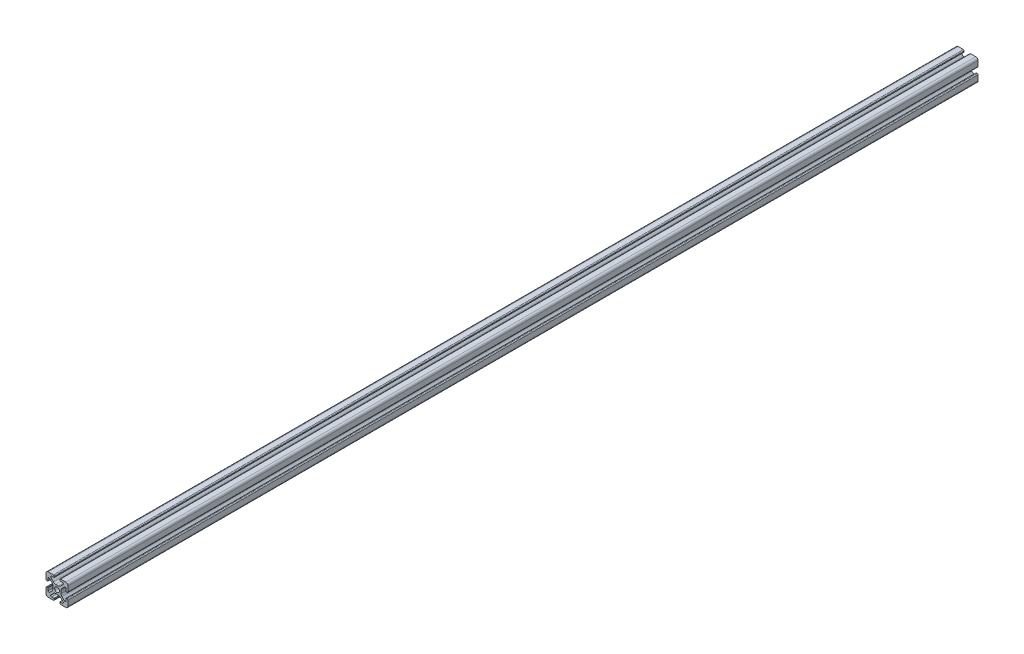
SolidWorks part; units mm, degrees
ref_plane "Plan de face" through (0, 0, 0) normal (0, 0, 1) x (1, 0, 0)
ref_plane "Plan de dessus" through (0, 0, 0) normal (0, 1, 0) x (1, 0, 0)
ref_plane "Plan de droite" through (0, 0, 0) normal (1, 0, 0) x (0, 0, -1)
ref_plane "Plan1" through (0, 0, 0) normal (0, 0, -1) x (-1, 0, 0)
sketch "Esquisse1" plane through (0, 0, 0) normal (0, 0, -1) x (-1, 0, 0)
  line L0 (-20, 6.7) -> (-20, 2)
  line L1 (-18, 0) -> (-13.3, 0)
  line L2 (-12.5, 0.8) -> (-12.5, 1.5)
  line L3 (-12.8, 1.8) -> (-14.9184, 1.8)
  line L4 (-15.5064, 3.2196) -> (-13.2547, 5.4713)
  line L5 (-11.1334, 6.35) -> (-8.8666, 6.35)
  line L6 (-6.7453, 5.4713) -> (-4.4936, 3.2196)
  line L7 (-5.0816, 1.8) -> (-7.2, 1.8)
  line L8 (-7.5, 1.5) -> (-7.5, 0.8)
  line L9 (-6.7, 0) -> (-2, 0)
  line L10 (0, 2) -> (0, 6.7)
  line L11 (-0.8, 7.5) -> (-1.5, 7.5)
  line L12 (-1.8, 7.2) -> (-1.8, 5.0816)
  line L13 (-3.2196, 4.4936) -> (-5.4713, 6.7453)
  line L14 (-6.35, 8.8666) -> (-6.35, 11.1334)
  line L15 (-5.4713, 13.2547) -> (-3.2196, 15.5064)
  line L16 (-1.8, 14.9184) -> (-1.8, 12.8)
  line L17 (-1.5, 12.5) -> (-0.8, 12.5)
  line L18 (0, 13.3) -> (0, 18)
  line L19 (-2, 20) -> (-6.7, 20)
  line L20 (-7.5, 19.2) -> (-7.5, 18.5)
  line L21 (-7.2, 18.2) -> (-5.0816, 18.2)
  line L22 (-4.4936, 16.7804) -> (-6.7453, 14.5287)
  line L23 (-8.8666, 13.65) -> (-11.1334, 13.65)
  line L24 (-13.2547, 14.5287) -> (-15.5064, 16.7804)
  line L25 (-14.9184, 18.2) -> (-12.8, 18.2)
  line L26 (-12.5, 18.5) -> (-12.5, 19.2)
  line L27 (-13.3, 20) -> (-18, 20)
  line L28 (-20, 18) -> (-20, 13.3)
  line L29 (-19.2, 12.5) -> (-18.5, 12.5)
  line L30 (-18.2, 12.8) -> (-18.2, 14.9184)
  line L31 (-16.7804, 15.5064) -> (-14.5287, 13.2547)
  line L32 (-13.65, 11.1334) -> (-13.65, 8.8666)
  line L33 (-14.5287, 6.7453) -> (-16.7804, 4.4936)
  line L34 (-18.2, 5.0816) -> (-18.2, 7.2)
  line L35 (-18.5, 7.5) -> (-19.2, 7.5)
  arc A0 (-19.2, 7.5) -> (-20, 6.7) centre (-19.2, 6.7) ccw
  arc A1 (-20, 2) -> (-18, 0) centre (-18, 2) ccw
  arc A2 (-13.3, 0) -> (-12.5, 0.8) centre (-13.3, 0.8) ccw
  arc A3 (-12.5, 1.5) -> (-12.8, 1.8) centre (-12.8, 1.5) ccw
  arc A4 (-14.9184, 1.8) -> (-15.5064, 3.2196) centre (-14.9184, 2.6316) cw
  arc A5 (-13.2547, 5.4713) -> (-11.1334, 6.35) centre (-11.1334, 3.35) cw
  arc A6 (-8.8666, 6.35) -> (-6.7453, 5.4713) centre (-8.8666, 3.35) cw
  arc A7 (-4.4936, 3.2196) -> (-5.0816, 1.8) centre (-5.0816, 2.6316) cw
  arc A8 (-7.2, 1.8) -> (-7.5, 1.5) centre (-7.2, 1.5) ccw
  arc A9 (-7.5, 0.8) -> (-6.7, 0) centre (-6.7, 0.8) ccw
  arc A10 (-2, 0) -> (0, 2) centre (-2, 2) ccw
  arc A11 (0, 6.7) -> (-0.8, 7.5) centre (-0.8, 6.7) ccw
  arc A12 (-1.5, 7.5) -> (-1.8, 7.2) centre (-1.5, 7.2) ccw
  arc A13 (-1.8, 5.0816) -> (-3.2196, 4.4936) centre (-2.6316, 5.0816) cw
  arc A14 (-5.4713, 6.7453) -> (-6.35, 8.8666) centre (-3.35, 8.8666) cw
  arc A15 (-6.35, 11.1334) -> (-5.4713, 13.2547) centre (-3.35, 11.1334) cw
  arc A16 (-3.2196, 15.5064) -> (-1.8, 14.9184) centre (-2.6316, 14.9184) cw
  arc A17 (-1.8, 12.8) -> (-1.5, 12.5) centre (-1.5, 12.8) ccw
  arc A18 (-0.8, 12.5) -> (0, 13.3) centre (-0.8, 13.3) ccw
  arc A19 (0, 18) -> (-2, 20) centre (-2, 18) ccw
  arc A20 (-6.7, 20) -> (-7.5, 19.2) centre (-6.7, 19.2) ccw
  arc A21 (-7.5, 18.5) -> (-7.2, 18.2) centre (-7.2, 18.5) ccw
  arc A22 (-5.0816, 18.2) -> (-4.4936, 16.7804) centre (-5.0816, 17.3684) cw
  arc A23 (-6.7453, 14.5287) -> (-8.8666, 13.65) centre (-8.8666, 16.65) cw
  arc A24 (-11.1334, 13.65) -> (-13.2547, 14.5287) centre (-11.1334, 16.65) cw
  arc A25 (-15.5064, 16.7804) -> (-14.9184, 18.2) centre (-14.9184, 17.3684) cw
  arc A26 (-12.8, 18.2) -> (-12.5, 18.5) centre (-12.8, 18.5) ccw
  arc A27 (-12.5, 19.2) -> (-13.3, 20) centre (-13.3, 19.2) ccw
  arc A28 (-18, 20) -> (-20, 18) centre (-18, 18) ccw
  arc A29 (-20, 13.3) -> (-19.2, 12.5) centre (-19.2, 13.3) ccw
  arc A30 (-18.5, 12.5) -> (-18.2, 12.8) centre (-18.5, 12.8) ccw
  arc A31 (-18.2, 14.9184) -> (-16.7804, 15.5064) centre (-17.3684, 14.9184) cw
  arc A32 (-14.5287, 13.2547) -> (-13.65, 11.1334) centre (-16.65, 11.1334) cw
  arc A33 (-13.65, 8.8666) -> (-14.5287, 6.7453) centre (-16.65, 8.8666) cw
  arc A34 (-16.7804, 4.4936) -> (-18.2, 5.0816) centre (-17.3684, 5.0816) cw
  arc A35 (-18.2, 7.2) -> (-18.5, 7.5) centre (-18.5, 7.2) ccw
  circle A36 centre (-10, 10) radius 2.15
extrude "Boss.-Extru.1" add sketch "Esquisse1" against normal blind 827
